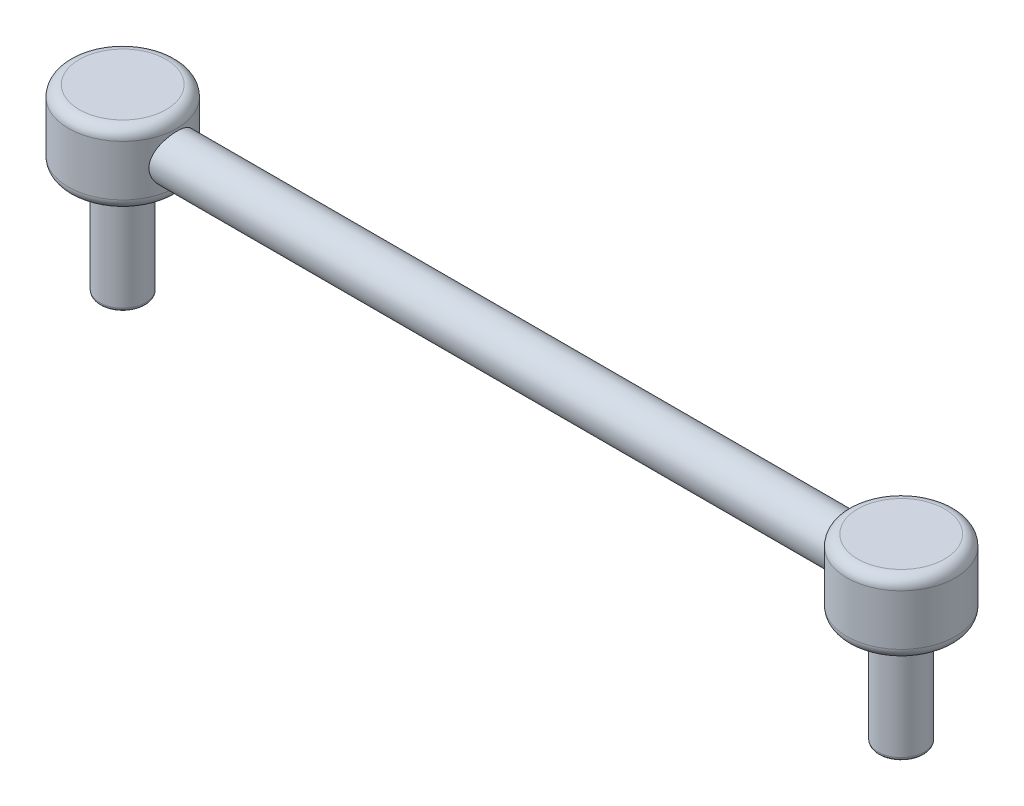
SolidWorks part; units mm, degrees
ref_plane "Front Plane" through (0, 0, 0) normal (0, 0, 1) x (1, 0, 0)
ref_plane "Top Plane" through (0, 0, 0) normal (0, 1, 0) x (1, 0, 0)
ref_plane "Right Plane" through (0, 0, 0) normal (1, 0, 0) x (0, 0, -1)
sketch "Sketch1" plane through (0, 0, 0) normal (0, 1, 0) x (1, 0, 0)
  circle A0 centre (0, 0) radius 6.35
  dimension "D1" = 12.7
extrude "Boss-Extrude1" add sketch "Sketch1" against normal blind 30
sketch "Sketch2" plane through (0, 0, 0) normal (0, 1, 0) x (1, 0, 0)
  circle A0 centre (0, 0) radius 15
  dimension "D1" = 30
extrude "Boss-Extrude2" add sketch "Sketch2" along normal blind 20
sketch "Sketch3" plane through (0, 0, 0) normal (0, 1, 0) x (1, 0, 0)
  point P0 (215, 0)
  dimension "D1" = 215
sketch "Sketch4" plane through (0, 0, 0) normal (0, 1, 0) x (1, 0, 0)
  circle A0 centre (215, 0) radius 6.35
  dimension "D1" = 12.7
extrude "Boss-Extrude3" add sketch "Sketch4" against normal blind 30 separate body
sketch "Sketch5" plane through (0, 0, 0) normal (0, 1, 0) x (1, 0, 0)
  circle A0 centre (215, 0) radius 15
  dimension "D1" = 30
extrude "Boss-Extrude4" add sketch "Sketch5" along normal blind 20
sketch "Sketch6" plane through (0, 0, 0) normal (1, 0, 0) x (0, 0, -1)
  circle A0 centre (0, 10) radius 6.35
  dimension "D1" = 12.7
  dimension "D2" = 10
extrude "Boss-Extrude5" add sketch "Sketch6" along normal blind 215
fillet "Fillet1" radius 3 4 edges at (215, 0, 15) (0, 0, 15) (0, 20, 15) (215, 20, 15)
fillet "Fillet2" radius 1 2 edges at (215, -30, 6.35) (0, -30, 6.35)
equation "\"pegDiameter\"= 1in / 2"
equation "\"rodDiameter\"= 1in / 2"
equation "\"rodLength\"= 215mm"
equation "\"D1@Sketch1\"=\"pegDiameter\""
equation "\"D1@Sketch3\"=\"rodLength\""
equation "\"D1@Sketch4\"=\"pegDiameter\""
equation "\"D1@Sketch6\"=\"rodDiameter\""
equation "\"D1@Boss-Extrude5\"=\"rodLength\""
